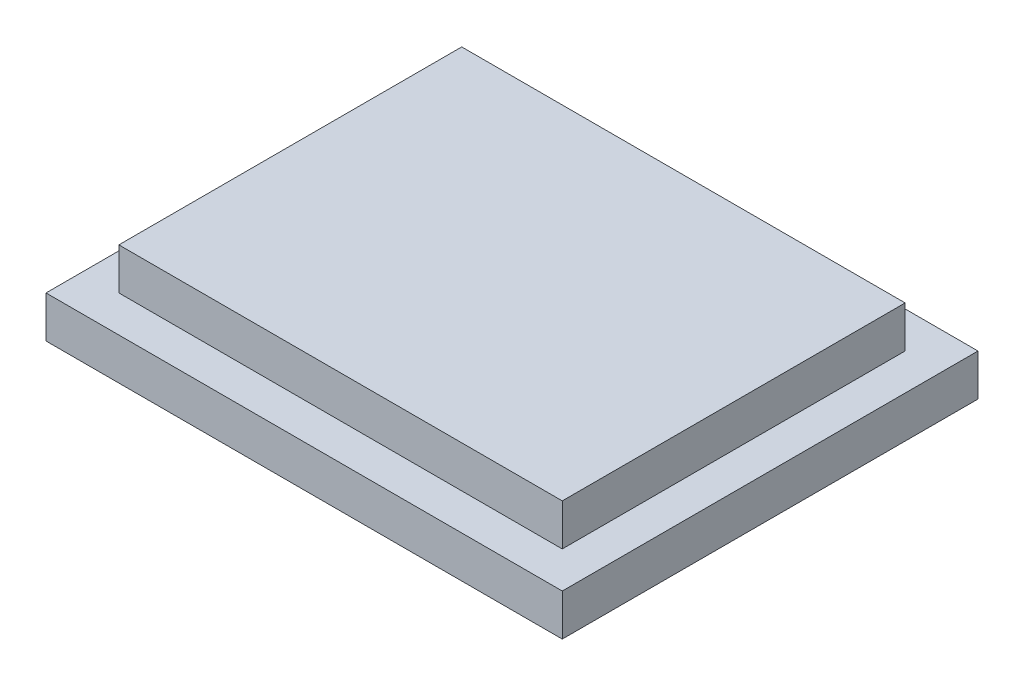
SolidWorks part; units mm, degrees
ref_plane "Front Plane" through (0, 0, 0) normal (0, 0, 1) x (1, 0, 0)
ref_plane "Top Plane" through (0, 0, 0) normal (0, 1, 0) x (1, 0, 0)
ref_plane "Right Plane" through (0, 0, 0) normal (1, 0, 0) x (0, 0, -1)
sketch "Sketch1" plane through (0, 0, 0) normal (0, 1, 0) x (1, 0, 0)
  line L1 (0, 0) -> (24.8, 0)
  line L2 (0, 0) -> (0, 19.97)
  line L3 (0, 19.97) -> (24.8, 19.97)
  line L4 (24.8, 0) -> (24.8, 19.97)
  dimension "D1" = 19.97
  dimension "D2" = 24.8
extrude "Boss-Extrude1" add sketch "Sketch1" along normal blind 2
sketch "Sketch2" plane through (0, 2, 0) normal (0, 1, 0) x (1, 0, 0)
  line L8 (1.75, 18.22) -> (1.75, 1.75)
  line L9 (1.75, 1.75) -> (23.05, 1.75)
  line L10 (23.05, 1.75) -> (23.05, 18.22)
  line L11 (23.05, 18.22) -> (1.75, 18.22)
  line L12 (1.75, 18.22) -> (1.75, 1.75)
  line L13 (1.75, 1.75) -> (23.05, 1.75)
  line L14 (23.05, 1.75) -> (23.05, 18.22)
  line L15 (23.05, 18.22) -> (1.75, 18.22)
  dimension "D1" = 1.75
extrude "Boss-Extrude2" add sketch "Sketch2" along normal blind 2
